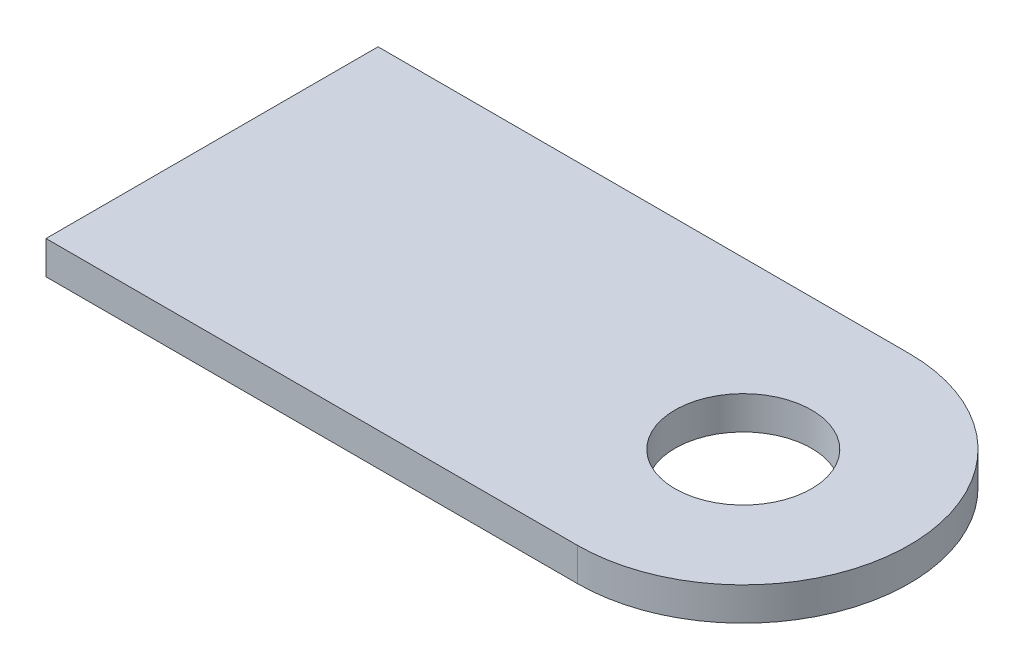
SolidWorks part; units mm, degrees
ref_plane "Front Plane" through (0, 0, 0) normal (0, 0, 1) x (1, 0, 0)
ref_plane "Top Plane" through (0, 0, 0) normal (0, 1, 0) x (1, 0, 0)
ref_plane "Right Plane" through (0, 0, 0) normal (1, 0, 0) x (0, 0, -1)
sketch "Sketch1" plane through (0, 0, 0) normal (0, 1, 0) x (1, 0, 0)
  line L0 (0, 0) -> (0, 15.875)
  line L1 (0, 15.875) -> (25.4, 15.875)
  line L2 (0, 0) -> (25.4, 0)
  arc A0 (25.4, 15.875) -> (25.4, 0) centre (25.4, 7.9375) cw
  circle A1 centre (25.4, 7.9375) radius 3.2639
  point P7 (0, 0)
  point P8 (0, 7.9375)
  point P9 (0, 0)
  dimension "D3" = 6.5278
  dimension "D1" = 15.875
  dimension "D2" = 25.4
extrude "Boss-Extrude1" add sketch "Sketch1" along normal blind 1.5875
